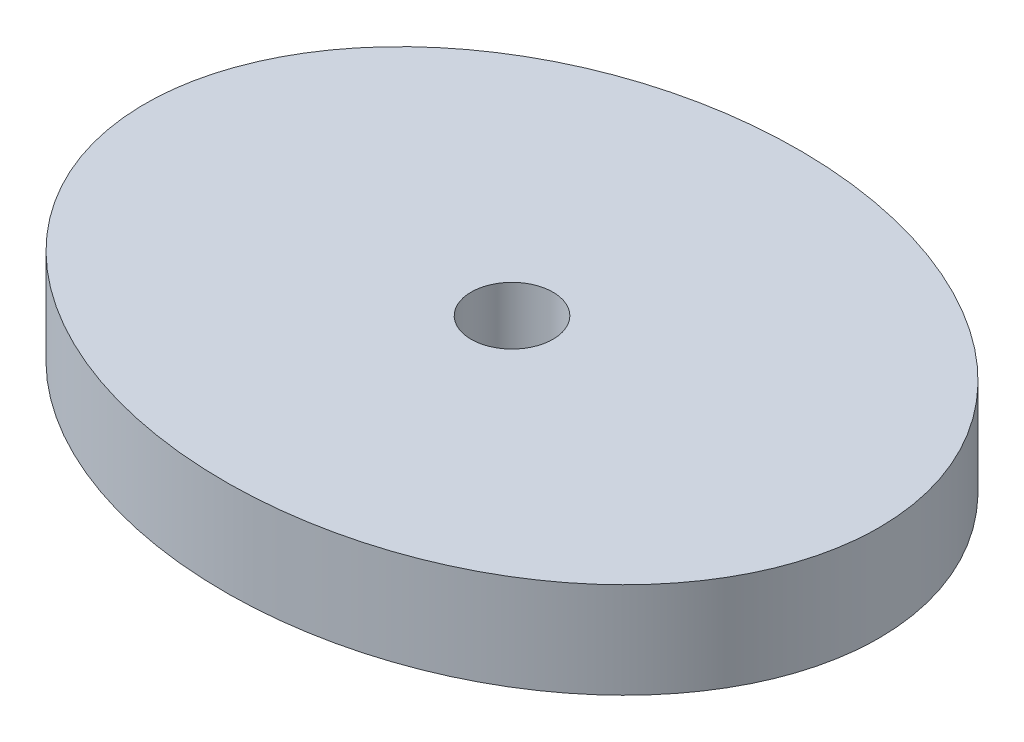
SolidWorks part; units mm, degrees
ref_plane "Front Plane" through (0, 0, 0) normal (0, 0, 1) x (1, 0, 0)
ref_plane "Top Plane" through (0, 0, 0) normal (0, 1, 0) x (1, 0, 0)
ref_plane "Right Plane" through (0, 0, 0) normal (1, 0, 0) x (0, 0, -1)
sketch "Sketch1" plane through (0, 0, 0) normal (0, 1, 0) x (1, 0, 0)
  line L0 (-19.175, 0) -> (19.175, 0) construction
  line L1 (0, 15) -> (0, -15) construction
  ellipse E0 centre (0, 0) end of major axis (19.175, 0) minor radius 15
  dimension "D1" = 38.35
  dimension "D2" = 30
extrude "Boss-Extrude1" add sketch "Sketch1" along normal blind 5
sketch "Sketch2" plane through (0, 5, 0) normal (0, 1, 0) x (1, 0, 0)
  circle A0 centre (0, 0) radius 2.1375
  dimension "D1" = 4.275
extrude "Cut-Extrude1" cut sketch "Sketch2" against normal blind 5
